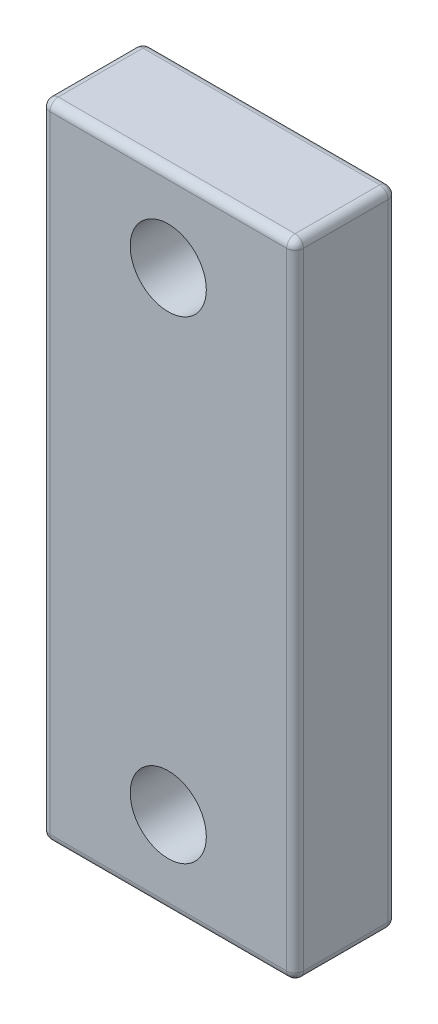
SolidWorks part; units mm, degrees
ref_plane "前视基准面" through (0, 0, 0) normal (0, 0, 1) x (1, 0, 0)
ref_plane "上视基准面" through (0, 0, 0) normal (0, 1, 0) x (1, 0, 0)
ref_plane "右视基准面" through (0, 0, 0) normal (1, 0, 0) x (0, 0, -1)
other "Configuration Table"
sketch "草图1" plane through (0, 0, 0) normal (0, 0, 1) x (1, 0, 0)
  line L0 (0, -14) -> (0, 14) construction
  line L1 (-7.5, -19) -> (7.5, -19)
  line L2 (-7.5, -19) -> (-7.5, 19)
  line L3 (-7.5, 19) -> (7.5, 19)
  line L4 (7.5, -19) -> (7.5, 19)
  line L5 (-7.5, -19) -> (7.5, 19) construction
  line L6 (-7.5, 19) -> (7.5, -19) construction
  circle A0 centre (0, 14) radius 2.25
  circle A1 centre (0, -14) radius 2.25
  point P0 (0, 0)
  point P9 (0, 0)
  dimension "D4" = 4.5
  dimension "D1" = 5
  dimension "D2" = 28
  dimension "D3" = 15
extrude "凸台-拉伸1" add sketch "草图1" along normal mid plane 6
fillet "圆角1" radius 0.5 12 edges at (0, -19, 3) (0, -19, -3) (7.5, -19, 0) (7.5, 0, 3) (7.5, 0, -3) (-7.5, 0, 3) (-7.5, -19, 0) (-7.5, 0, -3) (7.5, 19, 0) (0, 19, 3) (-7.5, 19, 0) (0, 19, -3)
sketch "草图2" plane through (0, 0, 0) normal (0, 1, 0) x (1, 0, 0)
  line L0 (-7, 3) -> (-4.5, 2)
  line L1 (-4.5, 2) -> (-2, 3)
  line L2 (-2, 3) -> (-7, 3)
  line L3 (-7, 3) -> (7, 3) construction
  point P5 (0, 0)
  dimension "D1" = 5
  dimension "D2" = 1
extrude "切除-拉伸1" cut sketch "草图2" against normal mid plane 21
pattern_linear "阵列(线性)1" count 3 spacing 4.5 along (1, 0, 0) of "切除-拉伸1"
